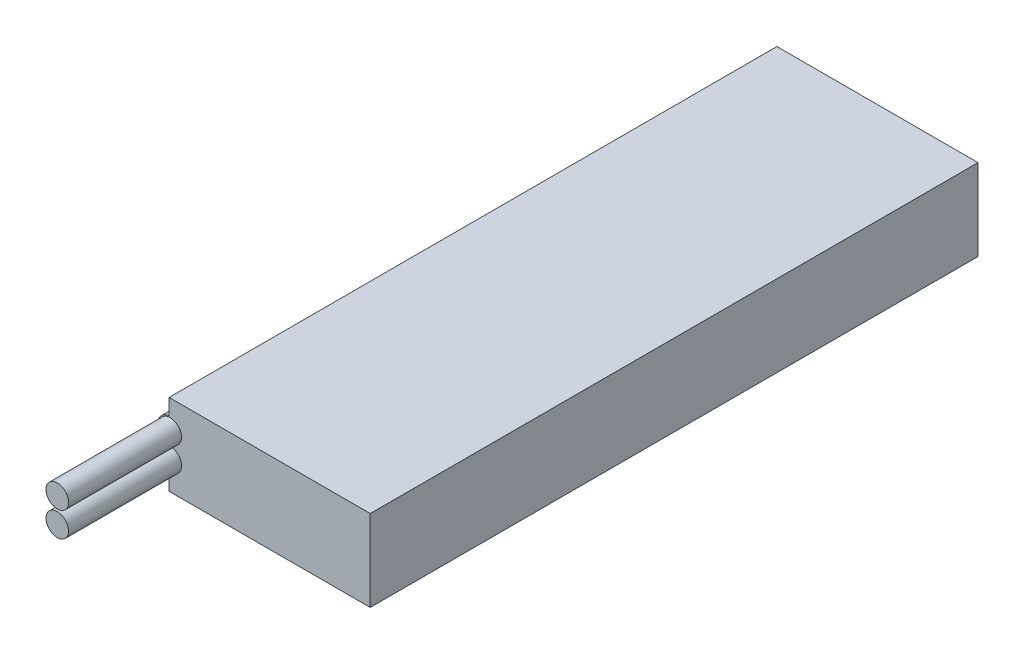
SolidWorks part; units mm, degrees
ref_plane "Front Plane" through (0, 0, 0) normal (0, 0, 1) x (1, 0, 0)
ref_plane "Top Plane" through (0, 0, 0) normal (0, 1, 0) x (1, 0, 0)
ref_plane "Right Plane" through (0, 0, 0) normal (1, 0, 0) x (0, 0, -1)
sketch "Sketch1" plane through (0, 0, 0) normal (0, 1, 0) x (1, 0, 0)
  line L1 (-22.25, -67.25) -> (22.25, -67.25)
  line L2 (-22.25, -67.25) -> (-22.25, 67.25)
  line L3 (-22.25, 67.25) -> (22.25, 67.25)
  line L4 (22.25, -67.25) -> (22.25, 67.25)
  line L5 (-22.25, -67.25) -> (22.25, 67.25) construction
  line L6 (-22.25, 67.25) -> (22.25, -67.25) construction
  point P0 (0, 0)
  dimension "D1" = 44.5
  dimension "D2" = 134.5
extrude "Boss-Extrude1" add sketch "Sketch1" along normal blind 18
sketch "Imagen" plane through (0, 18, 0) normal (0, 1, 0) x (1, 0, 0)
  line L0 (105.6667, 103.5) -> (539.1806, 103.5) construction
  line L1 (19, -59) -> (19, 75.5) construction
sketch "Sketch3" plane through (0, 0, 67.25) normal (0, 0, 1) x (1, 0, 0)
  line L0 (-22, 11.75) -> (-22, 6.25) construction
  line L1 (-24.75, 20.8788) -> (-24.75, -9.3152) construction
  line L3 (22.25, 18) -> (22.25, 0) construction
  line L4 (-22, 9) -> (22.25, 9) construction
  line L5 (-22.25, 14.4886) -> (-22.25, 3.5114)
  line L6 (-22.25, 18) -> (-22.25, 0) construction
  line L7 (-24.75, 11.75) -> (-24.75, 6.25)
  circle A0 centre (-22, 11.75) radius 2.75 construction
  circle A1 centre (-22, 6.25) radius 2.75 construction
  arc A2 (-22.25, 14.4886) -> (-24.75, 11.75) centre (-22, 11.75) ccw
  arc A3 (-22.25, 3.5114) -> (-24.75, 6.25) centre (-22, 6.25) cw
  line M9 (-22.25, 18) -> (-22.25, 0)
  dimension "D1" = 5.5
  dimension "D2" = 47
extrude "Boss-Extrude2" add sketch "Sketch3" against normal offset from surface (7 mm away) 127.5 contours A1 M9 | A0 M9 | A0 M9 | A1 M9
sketch "Sketch5" plane through (0, 0, 67.25) normal (0, 0, 1) x (1, 0, 0)
  arc A2 (-24.75, 6.25) -> (-22.25, 3.5114) centre (-22, 6.25) ccw construction
  arc A3 (-22.25, 14.4886) -> (-24.75, 11.75) centre (-22, 11.75) ccw construction
  circle A4 centre (-22, 6.25) radius 2.75 construction
  circle A5 centre (-22, 11.75) radius 2.75 construction
  circle A6 centre (-22, 11.75) radius 2.5
  circle A7 centre (-22, 6.25) radius 2.5
  dimension "D1" = 0.25
  dimension "D2" = 0.25
extrude "Boss-Extrude4" add sketch "Sketch5" along normal blind 25
